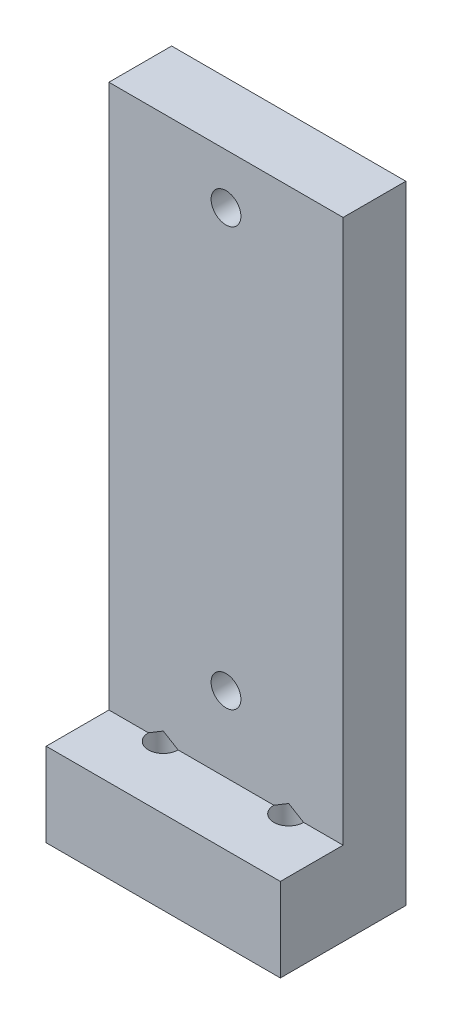
SolidWorks part; units mm, degrees
ref_plane "Front Plane" through (0, 0, 0) normal (0, 0, 1) x (1, 0, 0)
ref_plane "Top Plane" through (0, 0, 0) normal (0, 1, 0) x (1, 0, 0)
ref_plane "Right Plane" through (0, 0, 0) normal (1, 0, 0) x (0, 0, -1)
sketch "Sketch1" plane through (0, 0, 0) normal (0, 1, 0) x (1, 0, 0)
  line L1 (-8.89, -4.7625) -> (8.89, -4.7625)
  line L2 (-8.89, -4.7625) -> (-8.89, 4.7625)
  line L3 (-8.89, 4.7625) -> (8.89, 4.7625)
  line L4 (8.89, -4.7625) -> (8.89, 4.7625)
  line L5 (-8.89, -4.7625) -> (8.89, 4.7625) construction
  line L6 (-8.89, 4.7625) -> (8.89, -4.7625) construction
  point P0 (0, 0)
  dimension "D1" = 9.525
  dimension "D2" = 17.78
extrude "Boss-Extrude1" add sketch "Sketch1" along normal blind 47.625
sketch "Sketch2" plane through (0, 47.625, 0) normal (0, 1, 0) x (1, 0, 0)
  line L0 (8.89, -4.7625) -> (8.89, 4.7625) construction
  line L1 (-8.89, -4.7625) -> (8.89, -4.7625)
  line L2 (-8.89, -4.7625) -> (-8.89, 0)
  line L3 (-8.89, 0) -> (8.89, 0)
  line L4 (8.89, -4.7625) -> (8.89, 0)
  line L5 (8.89, 4.7625) -> (-8.89, 4.7625) construction
  dimension "D1" = 4.7625
extrude "Cut-Extrude1" cut sketch "Sketch2" against normal offset from surface (41.275 mm away) 6.35 up to face at (0, 0, 0)
hole_wizard "#4-40 Tapped Hole1" positions "Sketch4" profile "Sketch5" tap size "#4-40" standard "ANSI Inch"
sketch "Sketch4" plane through (0, 0, 0) normal (0, -1, 0) x (-1, 0, 0)
  line L4 (-4.7625, 0) -> (4.7625, 0) construction
  point P0 (-4.7625, 0)
  point P2 (4.7625, 0)
  dimension "D1" = 9.525
sketch "Sketch5" plane through (4.7625, 0, 0) normal (1, 0, 0) x (0, 0, -1)
  line L0 (0, 0) -> (0, 7.0292)
  line L1 (0, 7.0292) -> (1.1303, 6.35)
  line L2 (1.1303, 6.35) -> (1.1303, 0)
  line L5 (1.1303, 0) -> (0, 0)
  line L10 (0, 7.0292) -> (-1.1303, 6.35) construction
  line L11 (0, -6.35) -> (0, 107.95) construction
  dimension "Tap Drill Dia." = 2.2606
  dimension "Tap Drill Depth" = 6.35
  dimension "Drill Angle" = 118
cosmetic thread "Hole Thread1" parameters "D1"=5.588, "D2"=2.8448
cosmetic thread "Hole Thread2" parameters "D1"=5.588, "D2"=2.8448
sketch "Sketch8" plane through (0, 0, -4.7625) normal (0, 0, -1) x (-1, 0, 0)
  line L0 (-8.89, 47.625) -> (8.89, 47.625) construction
  circle A0 centre (0, 43.815) radius 1.1303
  circle A1 centre (0, 12.065) radius 1.1303
  dimension "D2" = 2.2606
  dimension "D3" = 2.2606
  dimension "D4" = 3.81
  dimension "D1" = 31.75
extrude "Cut-Extrude2" cut sketch "Sketch8" against normal through all
